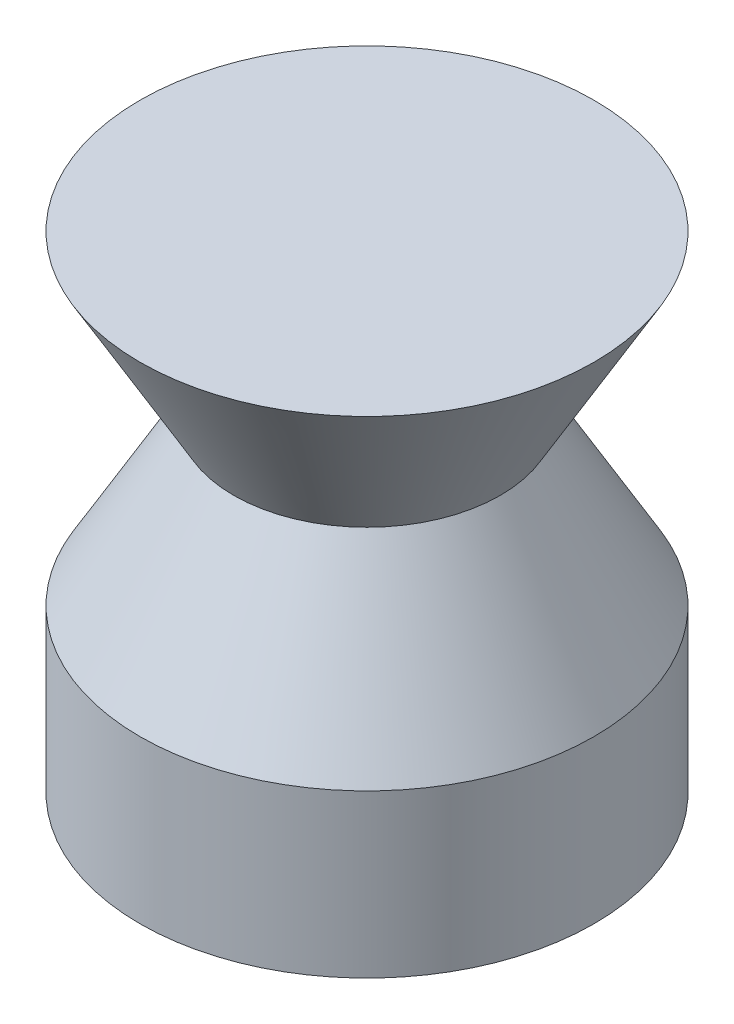
SolidWorks part; units mm, degrees
ref_plane "Front Plane" through (0, 0, 0) normal (0, 0, 1) x (1, 0, 0)
ref_plane "Top Plane" through (0, 0, 0) normal (0, 1, 0) x (1, 0, 0)
ref_plane "Right Plane" through (0, 0, 0) normal (1, 0, 0) x (0, 0, -1)
sketch "Sketch2" plane through (0, 0, 0) normal (0, 1, 0) x (1, 0, 0)
  line L1 (-4.7059, 4.1471) -> (-1.7059, 4.1471)
  line L2 (-4.7059, 4.1471) -> (-4.7059, -0.8529)
  line L3 (-4.7059, -0.8529) -> (-1.7059, -0.8529)
  line L4 (-1.7059, 4.1471) -> (-1.7059, -0.8529)
  circle A0 centre (-3.2059, 1.5769) radius 7
  dimension "D1" = 5
  dimension "D2" = 3
extrude "Boss-Extrude1" add sketch "Sketch2" along normal blind 5
sketch "Sketch3" plane through (0, 5, 0) normal (0, 1, 0) x (1, 0, 0)
  circle A0 centre (-3.2059, 1.5769) radius 7
extrude "Boss-Extrude2" add sketch "Sketch3" along normal blind 5 draft 30
sketch "Sketch4" plane through (0, 10, 0) normal (0, 1, 0) x (1, 0, 0)
  circle A0 centre (-3.2059, 1.5769) radius 4.1132
extrude "Boss-Extrude3" add sketch "Sketch4" along normal blind 5 draft 30 draft outward yes
